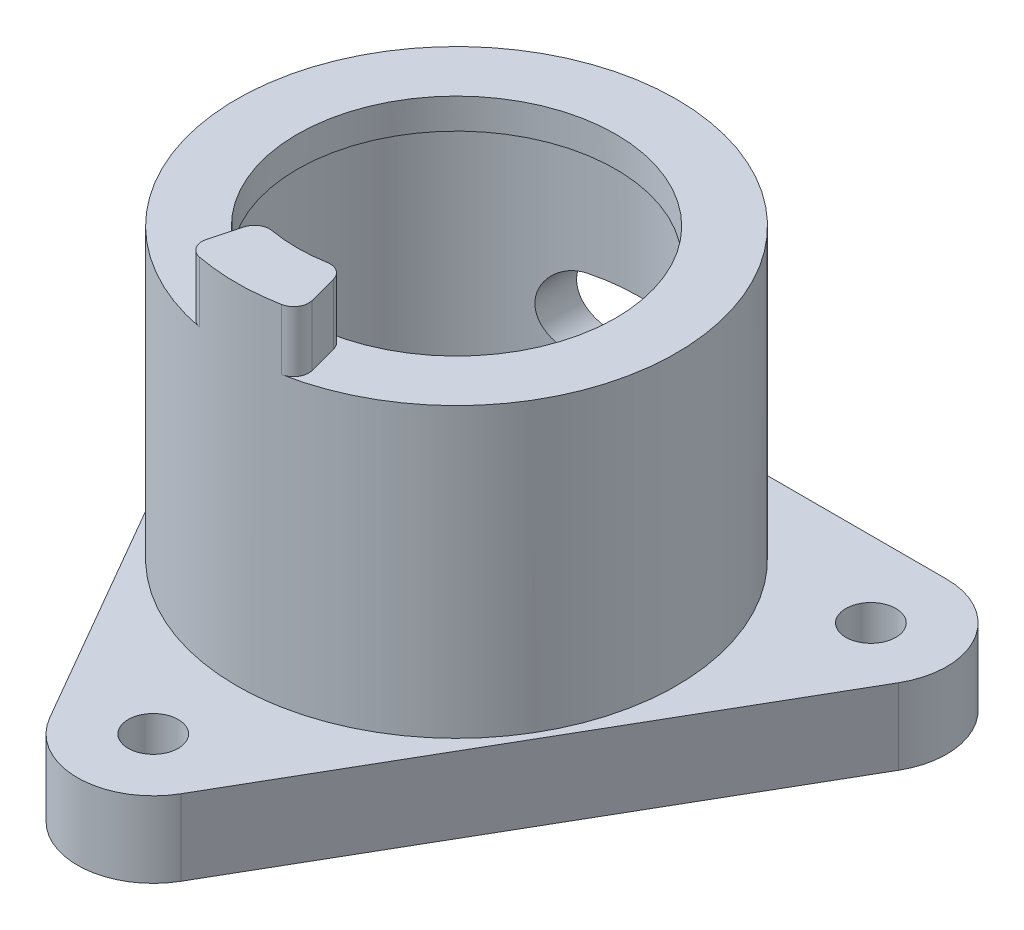
SolidWorks part; units mm, degrees
material "6061 合金"
ref_plane "前视基准面" through (0, 0, 0) normal (0, 0, 1) x (1, 0, 0)
ref_plane "上视基准面" through (0, 0, 0) normal (0, 1, 0) x (1, 0, 0)
ref_plane "右视基准面" through (0, 0, 0) normal (1, 0, 0) x (0, 0, -1)
sketch "草图1" plane through (0, 0, 0) normal (0, 1, 0) x (1, 0, 0)
  line L3 (-21.6506, 7.5) -> (-4.3301, -22.5)
  line L4 (21.6506, 7.5) -> (4.3301, -22.5)
  line L5 (17.3205, 15) -> (-17.3205, 15)
  arc A0 (-17.3205, 15) -> (-21.6506, 7.5) centre (-17.3205, 10) ccw
  arc A1 (21.6506, 7.5) -> (17.3205, 15) centre (17.3205, 10) ccw
  arc A2 (-4.3301, -22.5) -> (4.3301, -22.5) centre (0, -20) ccw
  circle A3 centre (0, 0) radius 12
  circle A4 centre (0, 0) radius 20 construction
  point P8 (0, 0)
  point P25 (0, 0)
  dimension "D1" = 3
  dimension "D2" = 24
  dimension "D3" = 40
extrude "凸台-拉伸4" add sketch "草图1" along normal blind 5
sketch "草图5" plane through (0, 5, 0) normal (0, 1, 0) x (1, 0, 0)
  circle A0 centre (0, -20) radius 1.25
  circle A1 centre (-17.3205, 10) radius 1.25
  circle A2 centre (17.3205, 10) radius 1.25
  point P11 (0, 0)
  dimension "D1" = 2.5
  dimension "D2" = 20
  dimension "D3" = 3
sketch "草图6" plane through (0, 5, 0) normal (0, 1, 0) x (1, 0, 0)
  circle A0 centre (0, 0) radius 12
  circle A1 centre (0, 0) radius 14.5
  dimension "D1" = 29
extrude "凸台-拉伸5" add sketch "草图6" along normal blind 17
sketch "草图7" plane through (0, 22, 0) normal (0, 1, 0) x (1, 0, 0)
  circle A0 centre (0, 0) radius 14.5
  circle A1 centre (0, 0) radius 10.5
  dimension "D1" = 21
  dimension "D2" = 29
extrude "凸台-拉伸6" add sketch "草图7" along normal blind 2
sketch "草图8" plane through (0, 24, 0) normal (0, 1, 0) x (1, 0, 0)
  line L0 (2.9651, -11.0661) -> (3.4845, -13.0042)
  line L2 (-2.9651, -11.0661) -> (-3.4845, -13.0042)
  arc A0 (-1.8254, -10.3401) -> (1.8254, -10.3401) centre (0, 0) ccw
  arc A1 (-2.7051, -14.2454) -> (2.7051, -14.2454) centre (0, 0) ccw
  arc A2 (2.9651, -11.0661) -> (1.8254, -10.3401) centre (1.9992, -11.3249) ccw
  arc A3 (2.7051, -14.2454) -> (3.4845, -13.0042) centre (2.5185, -13.263) ccw
  arc A4 (-2.7051, -14.2454) -> (-3.4845, -13.0042) centre (-2.5185, -13.263) cw
  arc A5 (-2.9651, -11.0661) -> (-1.8254, -10.3401) centre (-1.9992, -11.3249) cw
  dimension "D1" = 1
extrude "凸台-拉伸7" add sketch "草图8" along normal blind 4
sketch "草图9" plane through (0, 0, 0) normal (0, 0, 1) x (1, 0, 0)
  line L1 (-21.6506, 0) -> (-4.3301, 0) construction
  line L2 (-3, 14) -> (3, 14)
  line L3 (3, 9) -> (-3, 9)
  arc A0 (-3, 14) -> (-3, 9) centre (-3, 11.5) ccw
  arc A1 (3, 14) -> (3, 9) centre (3, 11.5) cw
  point P1 (0, 9)
  dimension "D1" = 5
  dimension "D2" = 6
  dimension "D3" = 11.5
extrude "切除-拉伸3" cut sketch "草图9" against normal through all
hole_wizard "M4 螺纹孔1" positions "3D草图1" profile "草图10" tap size "M4" standard "GB" end condition through all
sketch3d "3D草图1"
  point P0 (0, 5, 20)
  point P3 (17.3205, 5, -10)
  point P6 (-17.3205, 5, -10)
sketch "草图10" plane through (0, 5, 20) normal (1, 0, 0) x (0, 0, 1)
  line L0 (0, 0) -> (0, 5)
  line L1 (0, 5) -> (1.65, 5)
  line L2 (1.65, 5) -> (1.65, 0)
  line L5 (1.65, 0) -> (0, 0)
  line L11 (0, -6.35) -> (0, 107.95) construction
  dimension "通孔螺纹孔钻头直径" = 3.3
  dimension "通孔螺纹孔钻头深度" = 5
cosmetic thread "孔螺蚊线1" parameters "D2"=4
cosmetic thread "孔螺蚊线2" parameters "D2"=4
cosmetic thread "孔螺蚊线3" parameters "D2"=4
